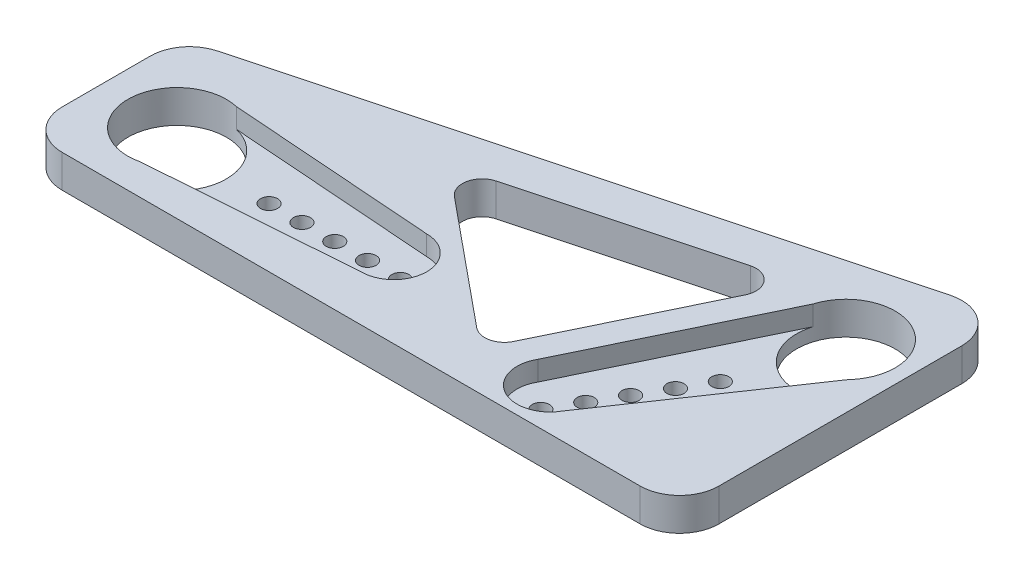
SolidWorks part; units mm, degrees
ref_plane "Front Plane" through (0, 0, 0) normal (0, 0, 1) x (1, 0, 0)
ref_plane "Top Plane" through (0, 0, 0) normal (0, 1, 0) x (1, 0, 0)
ref_plane "Right Plane" through (0, 0, 0) normal (1, 0, 0) x (0, 0, -1)
sketch "Sketch1" plane through (0, 0, 0) normal (0, 1, 0) x (1, 0, 0)
  line L0 (0, 0) -> (0, 12)
  line L1 (0, 12) -> (50, 25.3975)
  line L2 (0, 0) -> (50, 0)
  line L3 (50, 25.3975) -> (50, 0)
  line L4 (0, 6) -> (80.6022, 6) construction
  line L5 (24.75, 6) -> (24.75, 12.8953) construction
  line L6 (22.25, 8.5) -> (6.6102, 9.65)
  line L7 (22.25, 3.5) -> (6.6102, 2.35)
  line L8 (35.0626, 0) -> (46.15, 19.2039) construction
  line L9 (36.9162, 3.2106) -> (39.0813, 1.9606) construction
  line L10 (39.0813, 1.9606) -> (47.8971, 14.93)
  line L11 (36.9162, 3.2106) -> (34.7511, 4.4606) construction
  line L12 (34.7511, 4.4606) -> (41.5751, 18.58)
  line L13 (36.9162, 3.2106) -> (35.6662, 1.0455)
  line L14 (35.6662, 1.0455) -> (38.9704, -0.8622) construction
  line L16 (34.4162, 3.2106) -> (39.4162, 3.2106) construction
  circle A0 centre (5.75, 6) radius 3.75
  arc A1 (22.25, 3.5) -> (22.25, 8.5) centre (22.25, 6) ccw
  circle A2 centre (22.75, 6) radius 0.65
  circle A7 centre (45.1662, 17.5) radius 3.75
  arc A8 (34.7511, 4.4606) -> (39.4162, 3.2106) centre (36.9162, 3.2106) ccw
  circle A9 centre (36.6662, 2.7776) radius 0.65
  circle A10 centre (37.9162, 4.9426) radius 0.65
  circle A11 centre (39.1662, 7.1077) radius 0.65
  circle A12 centre (40.4162, 9.2728) radius 0.65
  circle A13 centre (41.6662, 11.4378) radius 0.65
  circle A14 centre (20.25, 6) radius 0.65
  circle A15 centre (17.75, 6) radius 0.65
  circle A16 centre (15.25, 6) radius 0.65
  circle A17 centre (12.75, 6) radius 0.65
  dimension "D4" = 7.5
  dimension "D5" = 5
  dimension "D6" = 5.75
  dimension "D7" = 19
  dimension "D9" = 2
  dimension "D10" = 1.3
  dimension "D12" = 5
  dimension "D16" = 7.5
  dimension "D17" = 5
  dimension "D20" = 30
  dimension "D22" = 17.5
  dimension "D24" = 2
  dimension "D11" = 1.3
  dimension "D25" = 5
  dimension "D27" = 5
  dimension "D1" = 12
  dimension "D2" = 15
  dimension "D3" = 50
  dimension "D8" = 7.3
  dimension "D13" = 12.8953
  dimension "D14" = 60
  dimension "D15" = 22.1748
  dimension "D18" = 7.3
  dimension "D19" = 19
  dimension "D21" = 4.8338
  dimension "D23" = 0.8622
  dimension "D28" = 80.6022
  dimension "D26" = 5
extrude "Boss-Extrude1" add sketch "Sketch1" along normal blind 2.5
sketch "Sketch2" plane through (0, 2.5, 0) normal (0, 1, 0) x (1, 0, 0)
  line L0 (6.6102, 9.65) -> (22.25, 8.5)
  line L1 (6.6102, 2.35) -> (22.25, 3.5)
  line L2 (45.1662, 17.5) -> (35.0626, 0) construction
  line L3 (34.7511, 4.4606) -> (41.5751, 18.58)
  line L4 (39.0813, 1.9606) -> (47.8971, 14.93)
  arc A0 (22.25, 3.5) -> (22.25, 8.5) centre (22.25, 6) ccw
  arc A1 (6.6102, 2.35) -> (6.6102, 9.65) centre (5.75, 6) ccw
  circle A2 centre (45.1662, 17.5) radius 3.75
  arc A3 (34.7511, 4.4606) -> (39.0813, 1.9606) centre (36.9162, 3.2106) ccw
  arc A4 (34.7511, 4.4606) -> (39.4162, 3.2106) centre (36.9162, 3.2106) ccw construction
  circle M2 centre (45.1662, 17.5) radius 3.75
  circle M3 centre (5.75, 6) radius 3.75
  circle M8 centre (12.75, 6) radius 0.65
  circle M9 centre (15.25, 6) radius 0.65
  circle M10 centre (17.75, 6) radius 0.65
  circle M11 centre (20.25, 6) radius 0.65
  circle M12 centre (22.75, 6) radius 0.65
  circle M13 centre (41.6662, 11.4378) radius 0.65
  circle M14 centre (40.4162, 9.2728) radius 0.65
  circle M15 centre (39.1662, 7.1077) radius 0.65
  circle M16 centre (37.9162, 4.9426) radius 0.65
  circle M17 centre (36.6662, 2.7776) radius 0.65
  dimension "D1" = 7.5
extrude "Cut-Extrude1" cut sketch "Sketch2" against normal blind 1.5 contours L1 A0 L0 M3 M9 M11 M12 M10 M8 | L2 A3 L4 M2 M13 M14 M15 M16 M17 | L2 A2 L3 A3 M17 M16 M15 M14 M13
fillet "Fillet1" radius 3 4 edges at (0, 1.25, 0) (0, 1.25, -12) (50, 1.25, -25.3975) (50, 1.25, 0)
sketch "Sketch3" plane through (0, 2.5, 0) normal (0, 1, 0) x (1, 0, 0)
  line L0 (2.2235, 12.5958) -> (46.2235, 24.3856) construction
  line L1 (18.5803, 13.8727) -> (39.8307, 19.5668)
  line L2 (39.8307, 19.5668) -> (31.8239, 3)
  line L3 (31.8239, 3) -> (18.5803, 13.8727)
  line L4 (3, 0) -> (47, 0) construction
  line L5 (34.7511, 4.4606) -> (41.5751, 18.58) construction
  dimension "D1" = 3
  dimension "D2" = 3
  dimension "D3" = 2
  dimension "D4" = 22
extrude "Cut-Extrude3" cut sketch "Sketch3" against normal through all
fillet "Fillet2" radius 1.5 3 edges at (31.8239, 1.25, -3) (39.8307, 1.25, -19.5668) (18.5803, 1.25, -13.8727)
